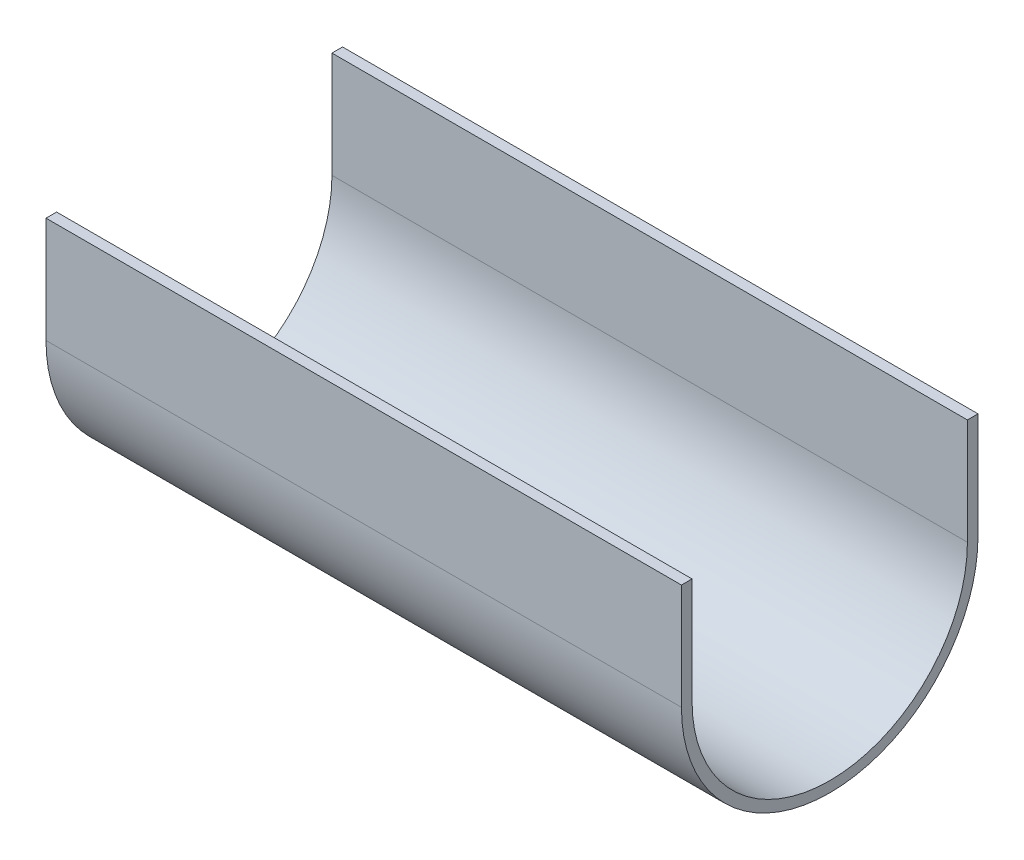
SolidWorks part; units mm, degrees
ref_plane "Front Plane" through (0, 0, 0) normal (0, 0, 1) x (1, 0, 0)
ref_plane "Top Plane" through (0, 0, 0) normal (0, 1, 0) x (1, 0, 0)
ref_plane "Right Plane" through (0, 0, 0) normal (1, 0, 0) x (0, 0, -1)
sketch "Sketch1" plane through (0, 0, 0) normal (1, 0, 0) x (0, 0, -1)
  line L0 (26, 0) -> (28, 0)
  line L5 (-28, 0) -> (-26, 0)
  arc A0 (26, 0) -> (-26, 0) centre (0, 0) cw
  arc A1 (28, 0) -> (-28, 0) centre (0, 0) cw
  dimension "D3" = 26
  dimension "D1" = 2
extrude "Boss-Extrude1" add sketch "Sketch1" along normal blind 120
sketch "Sketch2" plane through (0, 0, 0) normal (0, 1, 0) x (1, 0, 0)
  line L4 (0, 28) -> (0, 26)
  line L5 (0, 26) -> (120, 26)
  line L6 (120, 26) -> (120, 28)
  line L7 (120, 28) -> (0, 28)
  line L8 (0, 28) -> (0, 26)
  line L9 (0, 26) -> (120, 26)
  line L10 (120, 26) -> (120, 28)
  line L11 (120, 28) -> (0, 28)
  line L12 (0, -26) -> (0, -28)
  line L13 (0, -28) -> (120, -28)
  line L14 (120, -28) -> (120, -26)
  line L15 (120, -26) -> (0, -26)
  line L16 (0, -26) -> (0, -28)
  line L17 (0, -28) -> (120, -28)
  line L18 (120, -28) -> (120, -26)
  line L19 (120, -26) -> (0, -26)
  dimension "D1" = 0
  dimension "D2" = 0
extrude "Boss-Extrude2" add sketch "Sketch2" along normal blind 20
